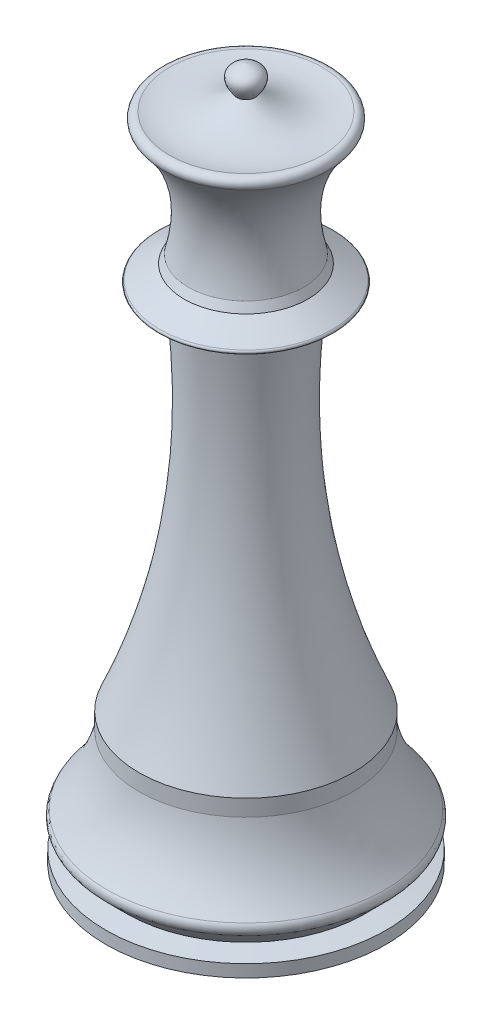
SolidWorks part; units mm, degrees
material "Maple"
ref_plane "Front Plane" through (0, 0, 0) normal (0, 0, 1) x (1, 0, 0)
ref_plane "Top Plane" through (0, 0, 0) normal (0, 1, 0) x (1, 0, 0)
ref_plane "Right Plane" through (0, 0, 0) normal (1, 0, 0) x (0, 0, -1)
sketch "Sketch1" plane through (0, 0, 0) normal (0, 0, 1) x (1, 0, 0)
  line L0 (0, 0) -> (17, 0)
  line L1 (0, 0) -> (0, 84) construction
  line L3 (17, 0) -> (17, 1.5)
  line L4 (17, 1.5) -> (14.4497, 1.9497)
  line L5 (14.4497, 1.9497) -> (17.5, 5)
  line L8 (12.9764, 16.03) -> (12.9764, 14.03)
  line L9 (-0.0236, 14.03) -> (12.9764, 14.03) construction
  line L10 (7, 60) -> (-0.0236, 60) construction
  line L11 (0, 84) -> (0, 0)
  line L15 (11, 61) -> (7, 60)
  line L16 (7, 64) -> (7.5, 63)
  line L17 (7.5, 63) -> (11, 61)
  line L18 (-0.0236, 63) -> (11, 63) construction
  line L19 (11, 63) -> (11, 60) construction
  line L20 (7, 60) -> (11, 60) construction
  arc A0 (0, 84) -> (0, 80.7715) centre (0.2641, 82.3857) cw construction
  spline S0 degree 2 poles (7, 64) (4.3965, 74.0703) (13, 80.5) knots 0 0 0 1 1 1
  spline S1 degree 2 poles (12.9764, 14.03) (13.9021, 8.7376) (17.5, 5) knots 0 0 0 1 1 1
  spline S2 degree 2 poles (7, 60) (4.136, 36.5954) (12.9764, 16.03) knots 0 0 0 1 1 1
  spline S3 degree 2 poles (13, 80.5) (6.4958, 76.7584) (1.1333, 81) knots 0 0 0 1 1 1
  spline S4 degree 2 poles (0, 84) (3.0265, 83.4156) (1.1333, 81) knots 0 0 0 1 1 1
  dimension "D1" = 17
  dimension "D2" = 1.5
  dimension "D3" = 0.5
  dimension "D4" = 55
  dimension "D5" = 5
  dimension "D6" = 100
  dimension "D14" = 13
  dimension "D17" = 3
  dimension "D18" = 1
  dimension "D19" = 1
  dimension "D9" = 84
  dimension "D10" = 14.03
  dimension "D8" = 2
  dimension "D7" = 60
  dimension "D11" = 7
  dimension "D12" = 7
  dimension "D13" = 16.5
  dimension "D15" = 11
  dimension "D16" = 13
  dimension "D20" = 1.5
  dimension "D21" = 7.5
  dimension "D22" = 2
revolve "Revolve1" add sketch "Sketch1" angle 360 about L11
fillet "Fillet1" radius 1 1 edges at (0, 5, 17.5)
fillet "Fillet2" radius 0.75 1 edges at (0, 80.5, 13)
fillet "Fillet3" radius 0.25 1 edges at (0, 61, 11)
equation "\"height\"= 84mm"
equation "\"baseRadius\"= 17mm"
equation "\"D1@Sketch1\"=\"baseRadius\""
equation "\"D14@Sketch1\"=\"baseRadius\"-4"
